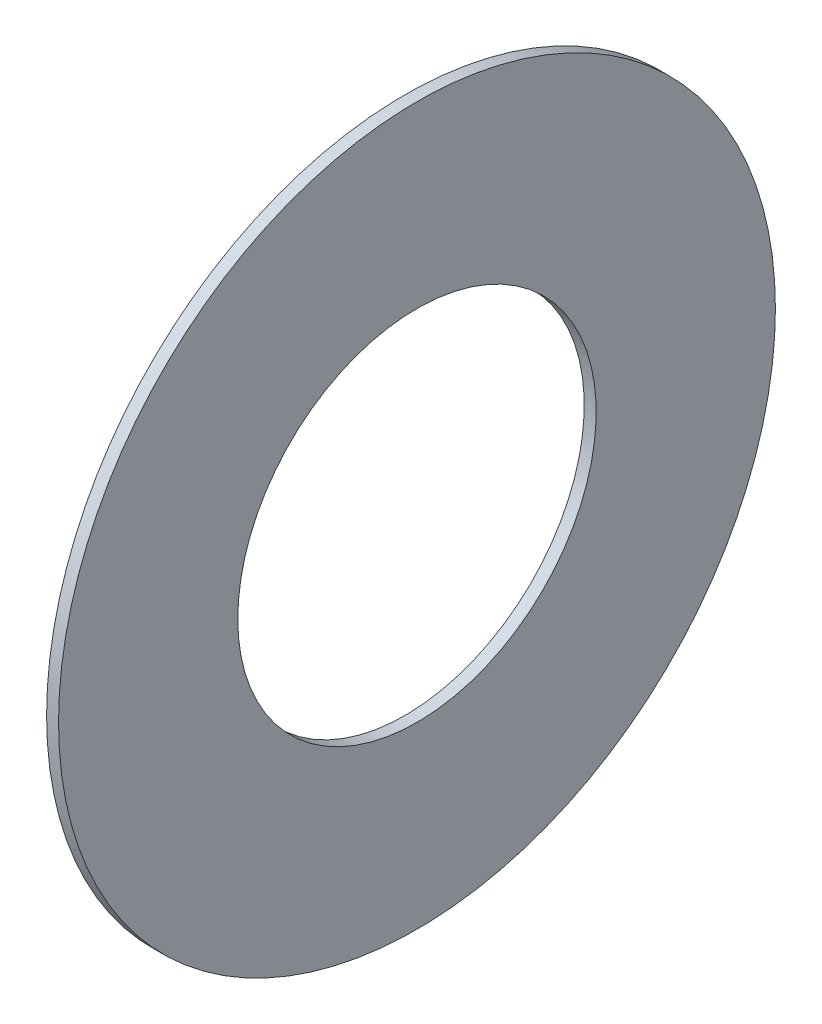
SolidWorks part; units mm, degrees
ref_plane "前视基准面" through (0, 0, 0) normal (0, 0, 1) x (1, 0, 0)
ref_plane "上视基准面" through (0, 0, 0) normal (0, 1, 0) x (1, 0, 0)
ref_plane "右视基准面" through (0, 0, 0) normal (1, 0, 0) x (0, 0, -1)
other "Configuration Table"
sketch "草图1" plane through (0, 0, 0) normal (1, 0, 0) x (0, 0, -1)
  circle A0 centre (0, 0) radius 30
  dimension "D1" = 60
extrude "凸台-拉伸1" add sketch "草图1" along normal blind 1
sketch "草图2" plane through (0, 0, 0) normal (-1, 0, 0) x (0, 0, 1)
  circle A0 centre (0, 0) radius 15
  dimension "D1" = 30
extrude "切除-拉伸1" cut sketch "草图2" against normal blind 1
